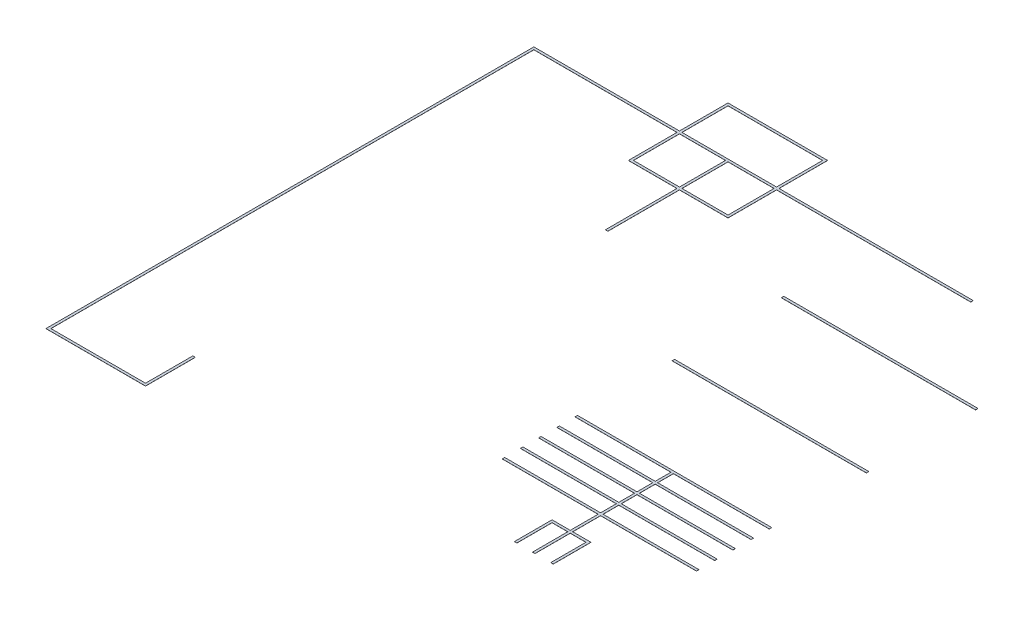
SolidWorks part; units mm, degrees
ref_plane "前视基准面" through (0, 0, 0) normal (0, 0, 1) x (1, 0, 0)
ref_plane "上视基准面" through (0, 0, 0) normal (0, 1, 0) x (1, 0, 0)
ref_plane "右视基准面" through (0, 0, 0) normal (1, 0, 0) x (0, 0, -1)
sketch "草图1" plane through (0, 0, 0) normal (0, 1, 0) x (1, 0, 0)
  line L0 (-2400.3124, 2800) -> (2399.6876, 2800) construction
  line L1 (-2400.3124, 2800) -> (-2400.3124, -2800) construction
  line L2 (-2400.3124, -2800) -> (2399.6876, -2800) construction
  line L3 (2399.6876, 2800) -> (2399.6876, -2800) construction
  line L6 (-2400.3124, 2000) -> (2399.6876, 2000) construction
  line L7 (-2400.3124, 1200) -> (2399.6876, 1200) construction
  line L8 (-2400.3124, 400) -> (2399.6876, 400) construction
  line L9 (-2400.3124, -400) -> (2399.6876, -400) construction
  line L10 (-2400.3124, -1200) -> (2399.6876, -1200) construction
  line L11 (-2400.3124, -2000) -> (2399.6876, -2000) construction
  line L12 (-1600.3124, 2800) -> (-1600.3124, -2800) construction
  line L13 (-800.3124, 2800) -> (-800.3124, -2800) construction
  line L14 (-0.3124, 2800) -> (-0.3124, -2800) construction
  line L15 (799.6876, 2800) -> (799.6876, -2800) construction
  line L16 (1599.6876, 2800) -> (1599.6876, -2800) construction
  point P0 (-0.3124, 0)
sketch "草图2" plane through (0, 0, 0) normal (0, 1, 0) x (1, 0, 0)
  line L0 (-0.3124, 2400) -> (-2000.3124, 2400) construction
  line L1 (-0.3124, 2800) -> (-0.3124, -2800) construction
  line L2 (-2400.3124, 2800) -> (-2400.3124, -2800) construction
  line L3 (-2000.3124, 2400) -> (-2000.3124, -1600) construction
  line L4 (-2400.3124, 2800) -> (2399.6876, 2800) construction
  line L5 (-2400.3124, -2800) -> (2399.6876, -2800) construction
  line L6 (-2010.3124, -1610) -> (-1190.3124, -1610)
  line L7 (-800.3124, 2800) -> (-800.3124, -2800) construction
  line L8 (-1200.3124, -1600) -> (-1200.3124, -1200) construction
  line L9 (-2400.3124, -1200) -> (2399.6876, -1200) construction
  line L10 (-800.3124, 2800) -> (-800.3124, 2000) construction
  line L11 (-2400.3124, 2000) -> (2399.6876, 2000) construction
  line L12 (-800.3124, 2000) -> (-0.3124, 2000) construction
  line L13 (-0.3124, 2000) -> (-0.3124, 2800) construction
  line L14 (-0.3124, 2800) -> (-800.3124, 2800) construction
  line L15 (-0.3124, 2400) -> (799.6876, 2400) construction
  line L16 (799.6876, 2800) -> (799.6876, -2800) construction
  line L17 (799.6876, 2400) -> (1599.6876, 2400) construction
  line L18 (1599.6876, 2800) -> (1599.6876, -2800) construction
  line L19 (-2010.3124, -1600) -> (-1200.3124, -1600) construction
  line L24 (-1190.3124, -2400) -> (-1190.3124, -1200) construction
  line L25 (-1200.3124, -2400) -> (-1200.3124, -1200) construction
  line L30 (-1990.3124, 2390) -> (-1990.3124, -2390) construction
  line L31 (-2000.3124, 2400) -> (-2000.3124, -2400) construction
  line L32 (-2010.3124, 2410) -> (-2010.3124, -2410) construction
  line L33 (1599.6876, 2400) -> (1599.6876, -1200) construction
  line L34 (1374.6876, -1050) -> (1824.6876, -1050) construction
  line L39 (-1190.3124, -1600) -> (-1190.3124, -1200)
  line L40 (-1210.3124, -1590) -> (-1210.3124, -1200)
  line L44 (-1190.3124, -1200) -> (-1210.3124, -1200)
  line L47 (1449.6876, -900) -> (1749.6876, -900) construction
  line L59 (1824.6876, -1200) -> (1374.6876, -1200) construction
  line L60 (9.6876, 2410) -> (799.6876, 2410)
  line L62 (1374.6876, -1200) -> (1374.6876, -1050) construction
  line L63 (1824.6876, -1200) -> (1824.6876, -1050) construction
  line L64 (1449.6876, -900) -> (1449.6876, -1200) construction
  line L67 (-10.3124, 2410) -> (-790.3124, 2410)
  line L68 (-2010.3124, 2410) -> (-2010.3124, -1600)
  line L70 (-810.3124, 2810) -> (-810.3124, 2410)
  line L71 (-810.3124, 1990) -> (-410.3124, 1990)
  line L72 (9.6876, 1990) -> (9.6876, 2390)
  line L73 (9.6876, 2810) -> (-810.3124, 2810)
  line L86 (9.6876, 2390) -> (799.6876, 2390)
  line L87 (-10.3124, 2390) -> (-390.3124, 2390)
  line L88 (-1990.3124, 2390) -> (-1990.3124, -1590)
  line L90 (-790.3124, 2790) -> (-790.3124, 2410)
  line L91 (-790.3124, 2010) -> (-410.3124, 2010)
  line L92 (-10.3124, 2010) -> (-10.3124, 2390)
  line L93 (-10.3124, 2790) -> (-790.3124, 2790)
  line L126 (-0.3124, 2410) -> (799.6876, 2410) construction
  line L127 (-0.3124, 2410) -> (-2010.3124, 2410) construction
  line L128 (9.6876, 2410) -> (9.6876, 2810)
  line L129 (9.6876, 1990) -> (9.6876, 2810) construction
  line L130 (-0.3124, 2390) -> (799.6876, 2390) construction
  line L131 (-0.3124, 2390) -> (-1990.3124, 2390) construction
  line L132 (-10.3124, 2410) -> (-10.3124, 2790)
  line L133 (-10.3124, 2010) -> (-10.3124, 2790) construction
  line L134 (-810.3124, 2410) -> (-2010.3124, 2410)
  line L135 (-790.3124, 2390) -> (-790.3124, 2010)
  line L136 (-790.3124, 2790) -> (-790.3124, 2010) construction
  line L137 (-810.3124, 2390) -> (-1990.3124, 2390)
  line L138 (-810.3124, 2390) -> (-810.3124, 1990)
  line L139 (-810.3124, 2810) -> (-810.3124, 1990) construction
  line L202 (-1990.3124, -2390) -> (-1200.3124, -2390) construction
  line L203 (-1210.3124, -2400) -> (-1210.3124, -1200) construction
  line L205 (1749.6876, -900) -> (1749.6876, -1200) construction
  line L233 (-400.3124, 2800) -> (-400.3124, 2790) construction
  line L234 (-400.3124, 2400) -> (-400.3124, 1400) construction
  line L235 (-410.3124, 2390) -> (-410.3124, 2010)
  line L236 (-390.3124, 2390) -> (-390.3124, 2010)
  line L238 (-410.3124, 1400) -> (-390.3124, 1400)
  line L239 (-410.3124, 2400) -> (-410.3124, 1400) construction
  line L240 (-410.3124, 2390) -> (-790.3124, 2390)
  line L241 (-390.3124, 2400) -> (-390.3124, 1400) construction
  line L242 (-390.3124, 2010) -> (-10.3124, 2010)
  line L243 (-790.3124, 2010) -> (-10.3124, 2010) construction
  line L244 (-410.3124, 1990) -> (-410.3124, 1400)
  line L245 (-390.3124, 1990) -> (-390.3124, 1400)
  line L246 (-390.3124, 1990) -> (9.6876, 1990)
  line L247 (-810.3124, 1990) -> (9.6876, 1990) construction
  line L254 (799.6876, -650) -> (2399.6876, -650) construction
  line L257 (2399.6876, 2800) -> (2399.6876, -2800) construction
  line L264 (-2400.3124, -400) -> (2399.6876, -400) construction
  line L265 (799.6876, -500) -> (2399.6876, -500) construction
  line L267 (799.6876, -350) -> (2399.6876, -350) construction
  line L273 (799.6876, -200) -> (2399.6876, -200) construction
  line L276 (799.6876, -50) -> (2399.6876, -50) construction
  line L291 (1589.6876, 2390) -> (1589.6876, 1660)
  line L294 (799.6876, -60) -> (1589.6876, -60)
  line L297 (799.6876, -210) -> (1589.6876, -210)
  line L300 (799.6876, -360) -> (1589.6876, -360)
  line L303 (799.6876, -510) -> (1589.6876, -510)
  line L306 (799.6876, -660) -> (1589.6876, -660)
  line L309 (1759.6876, -890) -> (1759.6876, -1200)
  line L312 (1439.6876, -890) -> (1589.6876, -890)
  line L315 (1439.6876, -890) -> (1439.6876, -1200)
  line L329 (-2000.3124, -2400) -> (-1200.3124, -2400) construction
  line L330 (-2010.3124, -2410) -> (-1200.3124, -2410) construction
  line L331 (-1990.3124, -1590) -> (-1210.3124, -1590)
  line L334 (-2010.3124, -1590) -> (-1190.3124, -1590) construction
  line L335 (-2010.3124, -1600) -> (-1190.3124, -1600) construction
  line L336 (-1190.3124, -1600) -> (-1190.3124, -1610)
  line L337 (-2010.3124, -1600) -> (-2010.3124, -1610)
  line L340 (1609.6876, 2410) -> (1609.6876, 1660)
  line L341 (799.6876, -40) -> (1589.6876, -40)
  line L342 (799.6876, -190) -> (1589.6876, -190)
  line L343 (799.6876, -340) -> (1589.6876, -340)
  line L344 (799.6876, -490) -> (1589.6876, -490)
  line L345 (799.6876, -640) -> (1589.6876, -640)
  line L346 (1739.6876, -910) -> (1739.6876, -1200)
  line L347 (1459.6876, -910) -> (1589.6876, -910)
  line L348 (1459.6876, -910) -> (1459.6876, -1200)
  line L350 (1589.6876, -1200) -> (1609.6876, -1200)
  line L351 (799.6876, -60) -> (799.6876, -40)
  line L352 (2399.6876, -60) -> (2399.6876, -40)
  line L353 (799.6876, -210) -> (799.6876, -190)
  line L354 (2399.6876, -210) -> (2399.6876, -190)
  line L355 (799.6876, -360) -> (799.6876, -340)
  line L356 (2399.6876, -360) -> (2399.6876, -340)
  line L357 (799.6876, -510) -> (799.6876, -490)
  line L358 (2399.6876, -510) -> (2399.6876, -490)
  line L359 (799.6876, -660) -> (799.6876, -640)
  line L360 (2399.6876, -660) -> (2399.6876, -640)
  line L361 (1759.6876, -1200) -> (1739.6876, -1200)
  line L362 (1439.6876, -1200) -> (1459.6876, -1200)
  line L363 (1609.6876, -40) -> (2399.6876, -40)
  line L364 (799.6876, -40) -> (2399.6876, -40) construction
  line L365 (1589.6876, -60) -> (1589.6876, -190)
  line L366 (1589.6876, 2390) -> (1589.6876, -1200) construction
  line L367 (1609.6876, -60) -> (2399.6876, -60)
  line L368 (799.6876, -60) -> (2399.6876, -60) construction
  line L369 (1609.6876, -60) -> (1609.6876, -190)
  line L370 (1609.6876, 2410) -> (1609.6876, -1200) construction
  line L371 (1609.6876, -190) -> (2399.6876, -190)
  line L372 (799.6876, -190) -> (2399.6876, -190) construction
  line L373 (1589.6876, -210) -> (1589.6876, -340)
  line L374 (1609.6876, -210) -> (1609.6876, -340)
  line L375 (1609.6876, -210) -> (2399.6876, -210)
  line L376 (799.6876, -210) -> (2399.6876, -210) construction
  line L377 (1609.6876, -340) -> (2399.6876, -340)
  line L378 (799.6876, -340) -> (2399.6876, -340) construction
  line L379 (1589.6876, -360) -> (1589.6876, -490)
  line L380 (1609.6876, -360) -> (2399.6876, -360)
  line L381 (799.6876, -360) -> (2399.6876, -360) construction
  line L382 (1609.6876, -360) -> (1609.6876, -490)
  line L383 (1609.6876, -490) -> (2399.6876, -490)
  line L384 (799.6876, -490) -> (2399.6876, -490) construction
  line L385 (1589.6876, -510) -> (1589.6876, -640)
  line L386 (1609.6876, -510) -> (2399.6876, -510)
  line L387 (799.6876, -510) -> (2399.6876, -510) construction
  line L388 (1609.6876, -510) -> (1609.6876, -640)
  line L389 (1609.6876, -640) -> (2399.6876, -640)
  line L390 (799.6876, -640) -> (2399.6876, -640) construction
  line L391 (1589.6876, -660) -> (1589.6876, -890)
  line L392 (1609.6876, -660) -> (2399.6876, -660)
  line L393 (799.6876, -660) -> (2399.6876, -660) construction
  line L394 (1609.6876, -660) -> (1609.6876, -890)
  line L395 (1609.6876, -890) -> (1759.6876, -890)
  line L396 (1439.6876, -890) -> (1759.6876, -890) construction
  line L397 (1589.6876, -910) -> (1589.6876, -1200)
  line L398 (1609.6876, -910) -> (1739.6876, -910)
  line L399 (1459.6876, -910) -> (1739.6876, -910) construction
  line L400 (1609.6876, -910) -> (1609.6876, -1200)
  line L401 (799.6876, 2410) -> (1609.6876, 2410) construction
  line L402 (799.6876, 2410) -> (1609.6876, 2410)
  line L403 (799.6876, 2390) -> (1589.6876, 2390)
  line L404 (799.6876, 2390) -> (1589.6876, 2390) construction
  line L405 (799.6876, 1650) -> (2399.6876, 1650) construction
  line L406 (799.6876, 750) -> (2399.6876, 750) construction
  line L407 (799.6876, 1640) -> (1589.6876, 1640)
  line L408 (799.6876, 740) -> (1589.6876, 740)
  line L409 (799.6876, 1660) -> (1589.6876, 1660)
  line L410 (799.6876, 760) -> (1589.6876, 760)
  line L411 (799.6876, 1640) -> (799.6876, 1660)
  line L412 (2399.6876, 1640) -> (2399.6876, 1660)
  line L413 (799.6876, 740) -> (799.6876, 760)
  line L414 (2399.6876, 740) -> (2399.6876, 760)
  line L415 (1609.6876, 1660) -> (2399.6876, 1660)
  line L416 (799.6876, 1660) -> (2399.6876, 1660) construction
  line L417 (1589.6876, 1640) -> (1589.6876, 760)
  line L418 (1609.6876, 1640) -> (2399.6876, 1640)
  line L419 (799.6876, 1640) -> (2399.6876, 1640) construction
  line L420 (1609.6876, 1640) -> (1609.6876, 760)
  line L421 (1609.6876, 760) -> (2399.6876, 760)
  line L422 (799.6876, 760) -> (2399.6876, 760) construction
  line L423 (1589.6876, 740) -> (1589.6876, -40)
  line L424 (1609.6876, 740) -> (2399.6876, 740)
  line L425 (799.6876, 740) -> (2399.6876, 740) construction
  line L426 (1609.6876, 740) -> (1609.6876, -40)
  point P62 (1599.6876, -1200)
  dimension "D1" = 400
  dimension "D2" = 400
  dimension "D3" = 10
  dimension "D4" = 400
  dimension "D5" = 10
  dimension "D6" = 10
  dimension "D8" = 150
  dimension "D9" = 150
  dimension "D10" = 450
  dimension "D11" = 150
  dimension "D12" = 150
  dimension "D14" = 250
  dimension "D15" = 5
  dimension "D16" = 150
  dimension "D17" = 10
  dimension "D19" = 900
  dimension "D20" = 800
  dimension "D21" = 1400
  dimension "D7" = 150
  dimension "D13" = 150
  dimension "D22" = 750
  dimension "D27" = 1200
  dimension "D29" = 10
  dimension "D23" = 10
  dimension "D24" = 10
  dimension "D25" = 10
  dimension "D26" = 10
  dimension "D28" = 10
  dimension "D18" = 10
  dimension "D30" = 10
extrude "凸台-拉伸1" add sketch "草图2" along normal blind 1
sketch "草图3" plane through (0, 0, 0) normal (0, 1, 0) x (1, 0, 0)
  line L0 (1609.6876, 760) -> (1609.6876, 1640) construction
  line L1 (1589.6876, 1640) -> (1589.6876, 760) construction
  line L2 (1609.6876, 760) -> (1609.6876, 1640)
  line L3 (1589.6876, 1640) -> (1589.6876, 760)
  line L4 (1589.6876, 1640) -> (1609.6876, 1640)
  line L5 (1589.6876, 760) -> (1609.6876, 760)
  line L6 (1589.6876, 2390) -> (1589.6876, 1660) construction
  line L7 (1589.6876, 2390) -> (1589.6876, 1660)
  line L8 (1609.6876, 1660) -> (1609.6876, 2410) construction
  line L9 (1609.6876, 1660) -> (1609.6876, 2390)
  line L10 (1589.6876, 2390) -> (1609.6876, 2390)
  line L11 (1589.6876, 1660) -> (1609.6876, 1660)
  line L12 (1589.6876, 740) -> (1589.6876, -40) construction
  line L13 (1589.6876, 740) -> (1589.6876, -40)
  line L14 (1609.6876, -40) -> (1609.6876, 740) construction
  line L15 (1609.6876, -40) -> (1609.6876, 740)
  line L16 (1589.6876, 740) -> (1609.6876, 740)
  line L17 (1589.6876, -40) -> (1609.6876, -40)
extrude "切除-拉伸2" cut sketch "草图3" against normal through all and the other way through all
